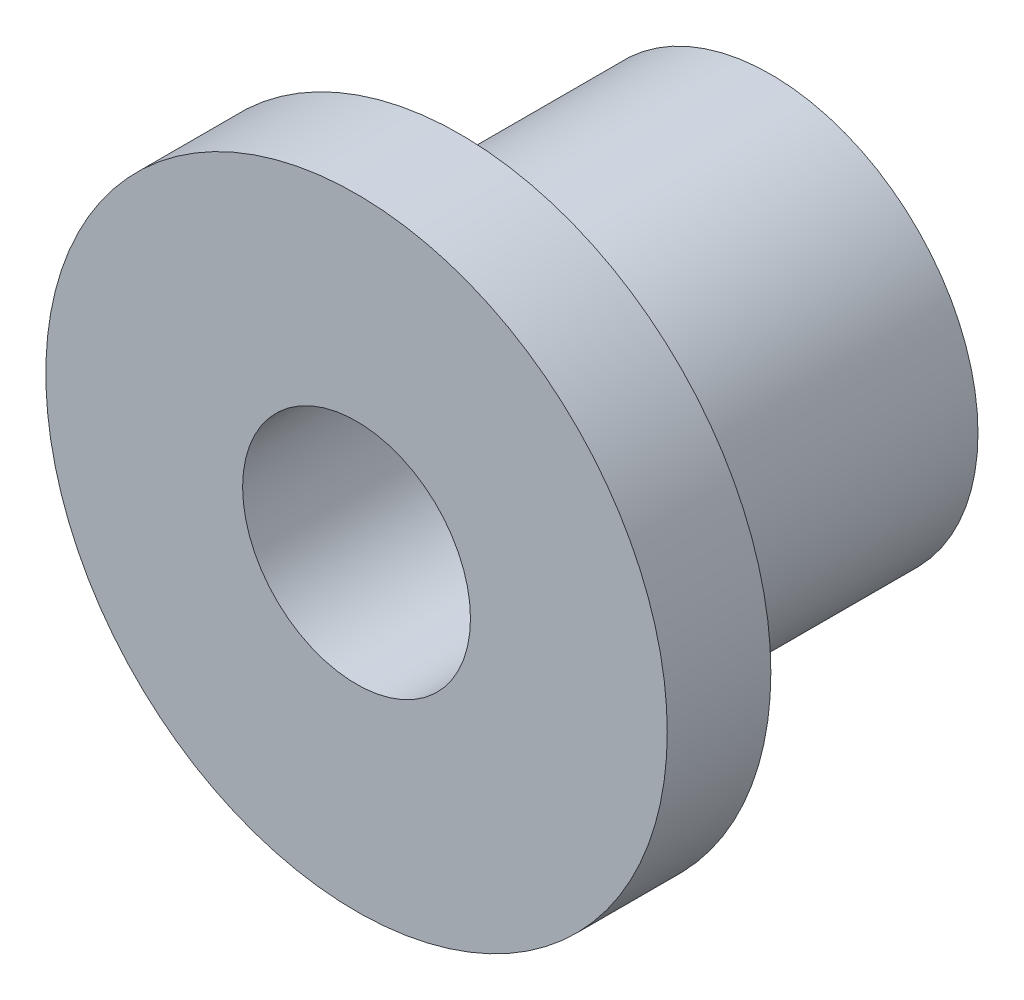
SolidWorks part; units mm, degrees
ref_plane "Front Plane" through (0, 0, 0) normal (0, 0, 1) x (1, 0, 0)
ref_plane "Top Plane" through (0, 0, 0) normal (0, 1, 0) x (1, 0, 0)
ref_plane "Right Plane" through (0, 0, 0) normal (1, 0, 0) x (0, 0, -1)
sketch "Sketch1" plane through (0, 0, 0) normal (0, 1, 0) x (1, 0, 0)
  line L0 (0, 0) -> (0, 5.4267) construction
  line L1 (1.65, 0) -> (1.65, 6)
  line L2 (1.65, 6) -> (3, 6)
  line L3 (3, 6) -> (3, 1.5)
  line L4 (3, 1.5) -> (4.5, 1.5)
  line L5 (4.5, 1.5) -> (4.5, 0)
  line L6 (4.5, 0) -> (1.65, 0)
  dimension "D1" = 6
  dimension "D2" = 3.3
  dimension "D3" = 9
  dimension "D4" = 6
  dimension "D5" = 1.5
revolve "Revolve1" add sketch "Sketch1" angle 360 about L0
fillet "Fillet1" radius 0.1 1 edges at (3, 0, -1.5)
